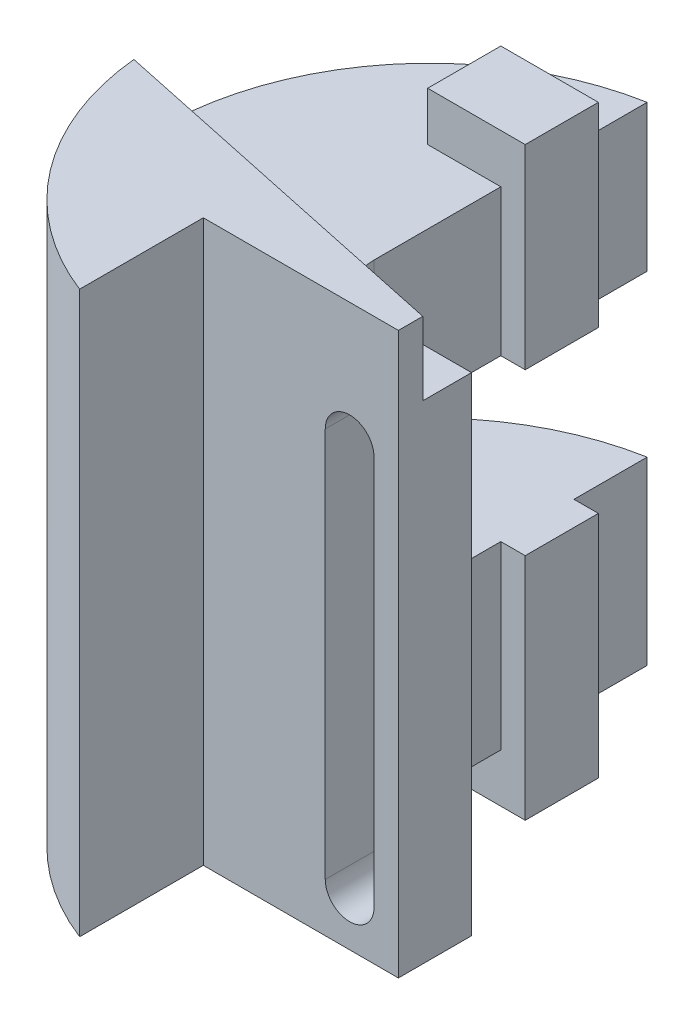
SolidWorks part; units mm, degrees
material "1060 Alloy"
ref_plane "Front Plane" through (0, 0, 0) normal (0, 0, 1) x (1, 0, 0)
ref_plane "Top Plane" through (0, 0, 0) normal (0, 1, 0) x (1, 0, 0)
ref_plane "Right Plane" through (0, 0, 0) normal (1, 0, 0) x (0, 0, -1)
sketch "Sketch1" plane through (0, 0, 0) normal (0, 1, 0) x (1, 0, 0)
  line L0 (0, 0) -> (-40, 0)
  line L1 (-40, 0) -> (-40, -25.3628)
  line L2 (0, 0) -> (0, 15)
  line L3 (0, 15) -> (-20, 15)
  line L4 (-30, 25) -> (-30, 81)
  arc A0 (-20, 15) -> (-30, 25) centre (-20, 25) cw
  arc A1 (-40, -25.3628) -> (-30, 81) centre (-20, 26.4083) cw
  dimension "D3" = 10
  dimension "D6" = 55.5
  dimension "D1" = 40
  dimension "D2" = 15
  dimension "D4" = 20
  dimension "D5" = 10
  dimension "D7" = 66
  dimension "D8" = 10
extrude "Boss-Extrude1" add sketch "Sketch1" along normal blind 115
sketch "Sketch2" plane through (0, 115, 0) normal (0, 1, 0) x (1, 0, 0)
  line L0 (0, 5) -> (-75.235, 20.9917)
  line L5 (0, 0) -> (0, 15)
  line L6 (0, 15) -> (-20, 15)
  line L7 (-30, 25) -> (-30, 81)
  line L8 (-40, -25.3628) -> (-40, 0)
  line L9 (-40, 0) -> (0, 0)
  line L10 (0, 5) -> (0, 15)
  line L11 (0, 15) -> (-20, 15)
  line L12 (-30, 25) -> (-30, 81)
  arc A2 (-30, 25) -> (-20, 15) centre (-20, 25) ccw
  arc A3 (-30, 81) -> (-40, -25.3628) centre (-20, 26.4083) ccw
  arc A4 (-30, 25) -> (-20, 15) centre (-20, 25) ccw
  arc A5 (-30, 81) -> (-75.235, 20.9917) centre (-20, 26.4083) ccw
  point P9 (0, 0)
  dimension "D2" = 5
  dimension "D3" = 78
  dimension "D1" = 0
extrude "Cut-Extrude1" cut sketch "Sketch2" against normal blind 15
sketch "Sketch3" plane through (0, 100, 0) normal (0, 1, 0) x (1, 0, 0)
  line L0 (-30, 25) -> (-30, 81) construction
  line L1 (-45, 66) -> (-25, 66)
  line L2 (-45, 66) -> (-45, 51)
  line L3 (-45, 51) -> (-25, 51)
  line L4 (-25, 66) -> (-25, 51)
  dimension "D1" = 5
  dimension "D2" = 20
  dimension "D3" = 15
  dimension "D4" = 15
extrude "Boss-Extrude2" add sketch "Sketch3" against normal blind 110 and the other way blind 10
sketch "Sketch4" plane through (0, 0, 0) normal (1, 0, 0) x (0, 0, -1)
  line L0 (81, 100) -> (81, 0) construction
  line L1 (81, 70) -> (41, 70)
  line L2 (81, 70) -> (81, 37)
  line L3 (81, 37) -> (41, 37)
  line L4 (41, 70) -> (41, 37)
  line L5 (66, 100) -> (81, 100) construction
  dimension "D1" = 33
  dimension "D2" = 30
  dimension "D3" = 40
extrude "Cut-Extrude2" cut sketch "Sketch4" against normal through all
sketch "Sketch5" plane through (0, 0, -15) normal (0, 0, -1) x (-1, 0, 0)
  line L0 (10, 90) -> (10, 10) construction
  line L1 (15, 90) -> (15, 10)
  line L2 (5, 90) -> (5, 10)
  line L3 (0, 100) -> (0, 0) construction
  arc A0 (15, 90) -> (5, 90) centre (10, 90) ccw
  arc A1 (5, 10) -> (15, 10) centre (10, 10) ccw
  point P2 (10, 50)
  point P7 (0, 0)
  dimension "D2" = 5
  dimension "D1" = 80
  dimension "D3" = 10
  dimension "D4" = 10
extrude "Cut-Extrude3" cut sketch "Sketch5" against normal through all
equation "\"a\"= 55.5mm"
equation "\"b\" = 66mm"
equation "\"c\"= 33mm"
